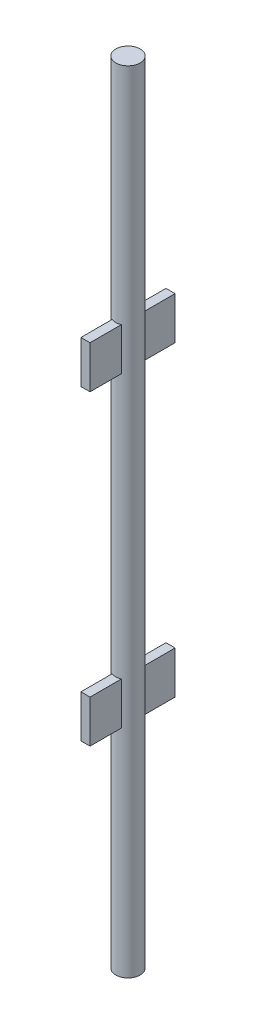
SolidWorks part; units mm, degrees
ref_plane "Plan de face" through (0, 0, 0) normal (0, 0, 1) x (1, 0, 0)
ref_plane "Plan de dessus" through (0, 0, 0) normal (0, 1, 0) x (1, 0, 0)
ref_plane "Plan de droite" through (0, 0, 0) normal (1, 0, 0) x (0, 0, -1)
sketch "Esquisse1" plane through (0, 0, 0) normal (0, 1, 0) x (1, 0, 0)
  circle A0 centre (0, 0) radius 20
  dimension "D1" = 40
extrude "Boss.-Extru.1" add sketch "Esquisse1" along normal blind 1300
sketch "Esquisse2" plane through (0, 0, 0) normal (0, 0, 1) x (1, 0, 0)
  line L0 (-20, 0) -> (-20, 90) construction
  line L1 (-20, 1300) -> (-20, 0) construction
  line L2 (-20, 1300) -> (-20, 1210) construction
  line L3 (-20, 90) -> (-20, 390) construction
  line L4 (-20, 390) -> (20, 390) construction
  line L5 (20, 0) -> (20, 1300) construction
  line L19 (7.5, 425) -> (-7.5, 425)
  line L20 (7.5, 425) -> (7.5, 355)
  line L21 (7.5, 355) -> (-7.5, 355)
  line L22 (-7.5, 425) -> (-7.5, 355)
  point P8 (0, 390)
  dimension "D1" = 90
  dimension "D2" = 90
  dimension "D3" = 300
  dimension "D4" = 15
extrude "Boss.-Extru.2" add sketch "Esquisse2" along normal mid plane 140
sketch "Esquisse4" plane through (0, 0, 0) normal (0, 0, 1) x (1, 0, 0)
  line L0 (0, 1300) -> (0, 930) construction
  line L1 (20, 1300) -> (-20, 1300) construction
  line L6 (7.5, 860) -> (-7.5, 860)
  line L7 (7.5, 860) -> (7.5, 930)
  line L8 (7.5, 930) -> (-7.5, 930)
  line L9 (-7.5, 860) -> (-7.5, 930)
  dimension "D1" = 370
  dimension "D2" = 15
  dimension "D3" = 70
extrude "Boss.-Extru.3" add sketch "Esquisse4" along normal mid plane 140
